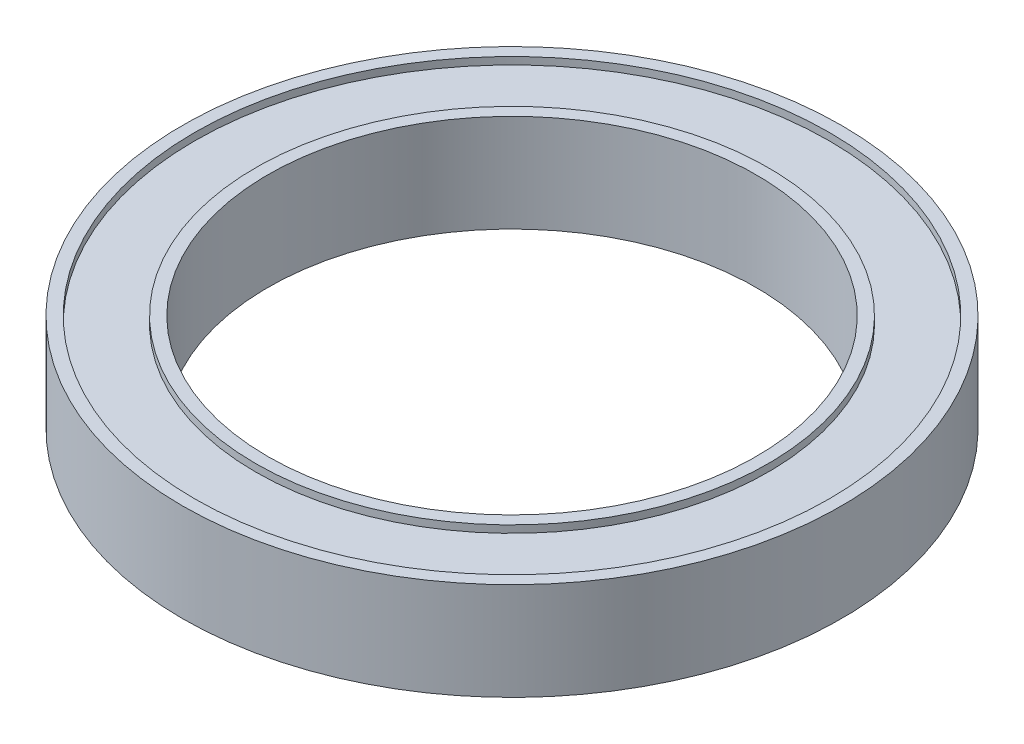
SolidWorks part; units mm, degrees
material "6061 合金"
ref_plane "前视基准面" through (0, 0, 0) normal (0, 0, 1) x (1, 0, 0)
ref_plane "上视基准面" through (0, 0, 0) normal (0, 1, 0) x (1, 0, 0)
ref_plane "右视基准面" through (0, 0, 0) normal (1, 0, 0) x (0, 0, -1)
sketch "草图1" plane through (0, 0, 0) normal (0, 1, 0) x (1, 0, 0)
  circle A0 centre (0, 0) radius 13.5
  circle A1 centre (0, 0) radius 10
  dimension "D1" = 27
  dimension "D2" = 20
extrude "凸台-拉伸1" add sketch "草图1" along normal blind 4
sketch "草图2" plane through (0, 4, 0) normal (0, 1, 0) x (1, 0, 0)
  circle A0 centre (0, 0) radius 13
  circle A1 centre (0, 0) radius 10.5
  circle A2 centre (0, 0) radius 13.5 construction
  circle A3 centre (0, 0) radius 10 construction
  dimension "D1" = 0.5
  dimension "D2" = 0.5
extrude "切除-拉伸1" cut sketch "草图2" against normal blind 0.3
ref_plane "基准面4" through (0, 2, 0) normal (0, 1, 0) x (1, 0, 0)
mirror "镜向1" about plane through (0, 2, 0) normal (0, 1, 0) of "切除-拉伸1"
